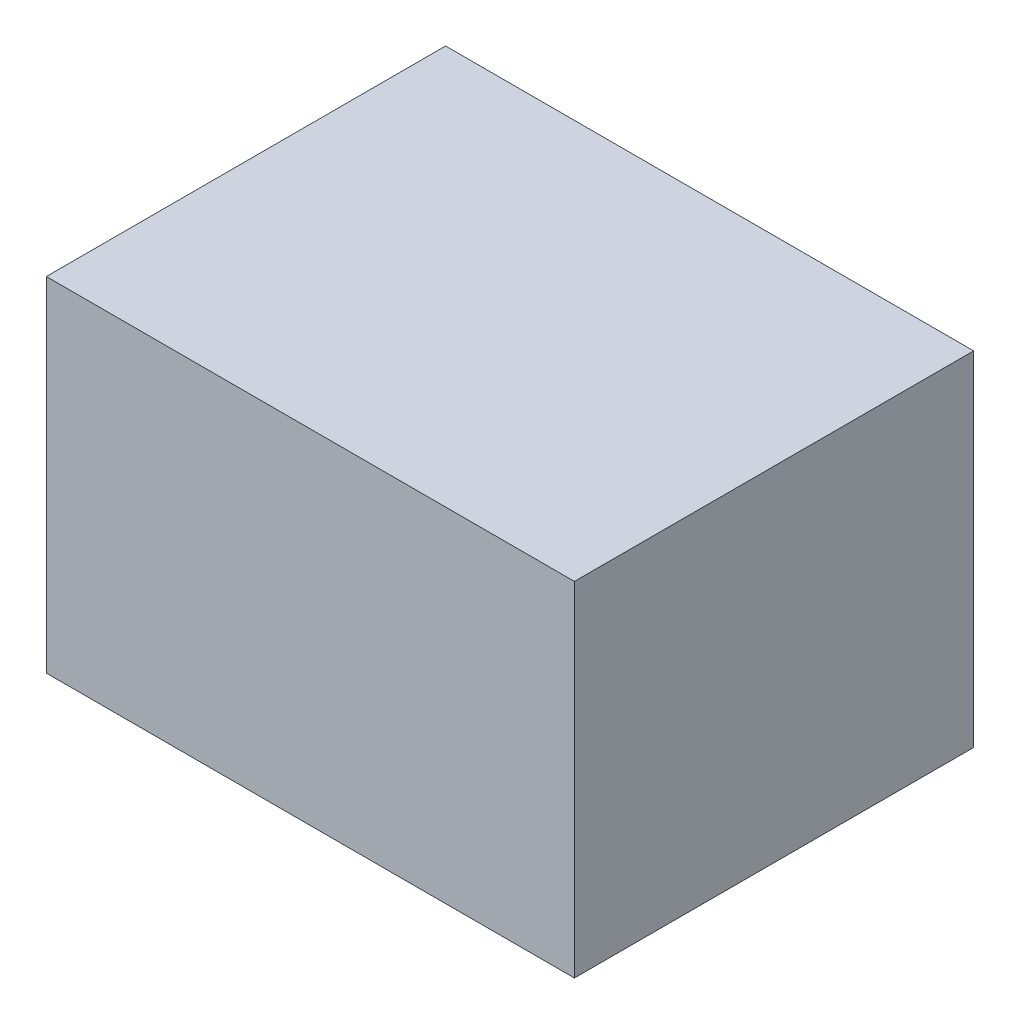
SolidWorks part; units mm, degrees
ref_plane "Front Plane" through (0, 0, 0) normal (0, 0, 1) x (1, 0, 0)
ref_plane "Top Plane" through (0, 0, 0) normal (0, 1, 0) x (1, 0, 0)
ref_plane "Right Plane" through (0, 0, 0) normal (1, 0, 0) x (0, 0, -1)
sketch "Sketch2" plane through (0, 0, 0) normal (0, 0, 1) x (1, 0, 0)
  line L1 (1548.0699, 1007.922) -> (-14.0301, 1007.922)
  line L2 (1548.0699, 1007.922) -> (1548.0699, -8.078)
  line L3 (1548.0699, -8.078) -> (-14.0301, -8.078)
  line L4 (-14.0301, 1007.922) -> (-14.0301, -8.078)
extrude "Boss-Extrude1" add sketch "Sketch2" along normal blind 1181.1 contours L1 L4 L3 L2
